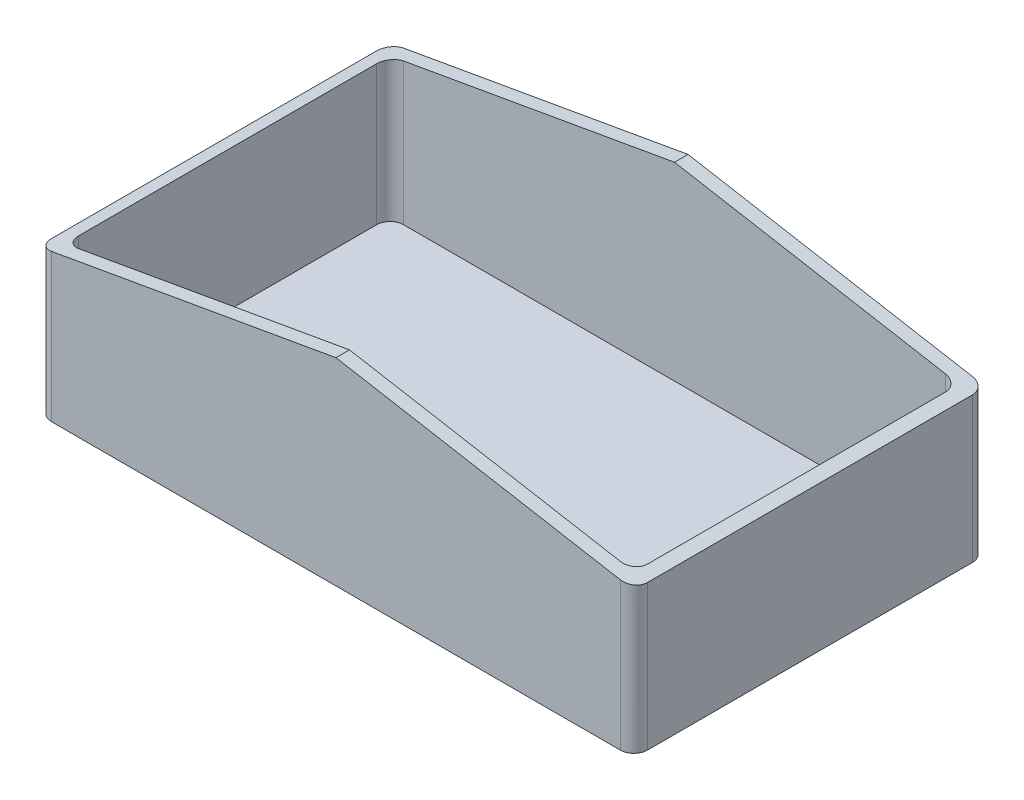
SolidWorks part; units mm, degrees
ref_plane "Спереди" through (0, 0, 0) normal (0, 0, 1) x (1, 0, 0)
ref_plane "Сверху" through (0, 0, 0) normal (0, 1, 0) x (1, 0, 0)
ref_plane "Справа" through (0, 0, 0) normal (1, 0, 0) x (0, 0, -1)
sketch "Эскиз1" plane through (0, 0, 0) normal (0, 1, 0) x (1, 0, 0)
  line L1 (-1050, -650) -> (1050, -650)
  line L2 (-1100, -600) -> (-1100, 600)
  line L3 (-1050, 650) -> (1050, 650)
  line L4 (1100, -600) -> (1100, 600)
  line L5 (-1100, -650) -> (1100, 650) construction
  line L6 (-1100, 650) -> (1100, -650) construction
  arc A0 (-1050, -650) -> (-1100, -600) centre (-1050, -600) cw
  arc A1 (1050, -650) -> (1100, -600) centre (1050, -600) ccw
  arc A2 (1050, 650) -> (1100, 600) centre (1050, 600) cw
  arc A3 (-1100, 600) -> (-1050, 650) centre (-1050, 600) cw
  point P0 (0, 0)
  dimension "D3" = 50
  dimension "D1" = 2200
  dimension "D2" = 1300
extrude "Бобышка-Вытянуть1" add sketch "Эскиз1" along normal blind 30
sketch "Эскиз2" plane through (0, 30, 0) normal (0, 1, 0) x (1, 0, 0)
  line L1 (-1050, -650) -> (1050, -650)
  line L2 (-1100, -600) -> (-1100, 600)
  line L3 (-1050, 650) -> (1050, 650)
  line L4 (1100, -600) -> (1100, 600)
  line L5 (-1100, -650) -> (1100, 650) construction
  line L6 (-1100, 650) -> (1100, -650) construction
  line L7 (-1000, -600) -> (1000, -600)
  line L8 (-1050, -550) -> (-1050, 550)
  line L9 (-1000, 600) -> (1000, 600)
  line L10 (1050, -550) -> (1050, 550)
  line L11 (-1050, -600) -> (1050, 600) construction
  line L12 (-1050, 600) -> (1050, -600) construction
  arc A0 (-1100, 600) -> (-1050, 650) centre (-1050, 600) cw
  arc A1 (-1050, 550) -> (-1000, 600) centre (-1000, 550) cw
  arc A2 (-1000, -600) -> (-1050, -550) centre (-1000, -550) cw
  arc A3 (-1050, -650) -> (-1100, -600) centre (-1050, -600) cw
  arc A4 (1050, -650) -> (1100, -600) centre (1050, -600) ccw
  arc A5 (1000, -600) -> (1050, -550) centre (1000, -550) ccw
  arc A6 (1000, 600) -> (1050, 550) centre (1000, 550) cw
  arc A7 (1050, 650) -> (1100, 600) centre (1050, 600) cw
  point P0 (0, 0)
  point P6 (0, 0)
  dimension "D5" = 50
  dimension "D1" = 2200
  dimension "D2" = 1300
  dimension "D3" = 50
  dimension "D4" = 50
extrude "Бобышка-Вытянуть2" add sketch "Эскиз2" along normal blind 700
sketch "Эскиз3" plane through (0, 0, 650) normal (0, 0, 1) x (1, 0, 0)
  line L0 (0, 730) -> (1300, 500.7749)
  line L1 (-1050, 730) -> (1050, 730) construction
  line L2 (-1300, 730) -> (1300, 730)
  line L3 (1300, 730) -> (1300, 500.7749)
  line L4 (0, 730) -> (0, 0) construction
  line L5 (-1300, 730) -> (-1300, 500.7749)
  line L6 (0, 730) -> (-1300, 500.7749)
  line M6 (1050, 0) -> (1050, 730)
  line M7 (1050, 730) -> (-1050, 730)
  line M8 (-1050, 730) -> (-1050, 0)
  dimension "D1" = 10
  dimension "D2" = 1300
extrude "Вырез-Вытянуть1" cut sketch "Эскиз3" against normal up to body separate body contours L6 M7 M8 | L6 L2 L5 M8 | L0 M7 M6 | L3 L2 L0 M6
